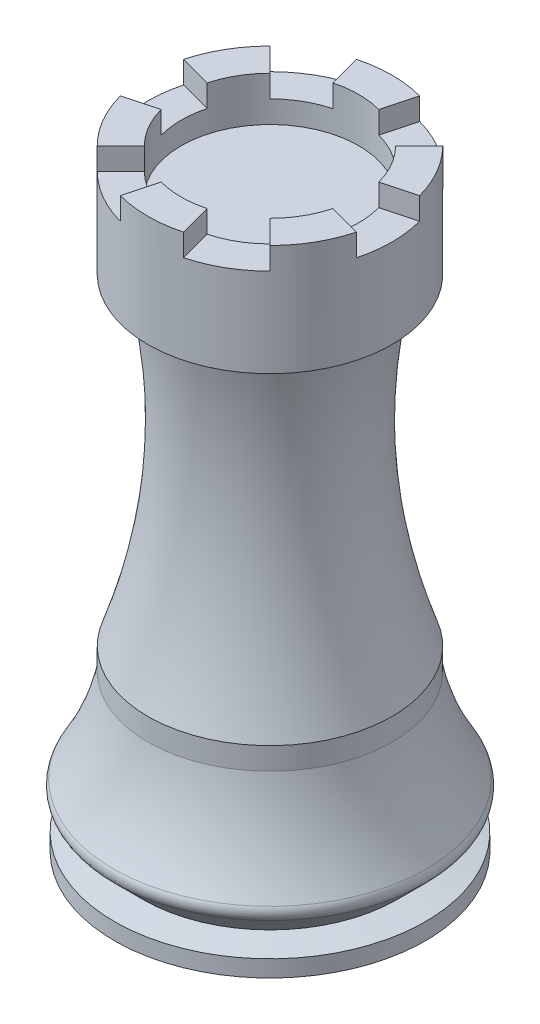
SolidWorks part; units mm, degrees
material "Maple"
ref_plane "Front Plane" through (0, 0, 0) normal (0, 0, 1) x (1, 0, 0)
ref_plane "Top Plane" through (0, 0, 0) normal (0, 1, 0) x (1, 0, 0)
ref_plane "Right Plane" through (0, 0, 0) normal (1, 0, 0) x (0, 0, -1)
sketch "bottom design" plane through (0, 0, 0) normal (0, 0, 1) x (1, 0, 0)
  line L0 (0, 0) -> (0, 50)
  line L1 (0, 0) -> (12, 0)
  line L2 (12, 0) -> (12, 3.0957) construction
  line L3 (0, 36) -> (9, 36) construction
  line L4 (9, 36) -> (9, 32.5) construction
  line L5 (9, 32.5) -> (0, 32.5) construction
  line L6 (12, 0) -> (12, 1.5)
  line L7 (12, 1.5) -> (9.8747, 1.8747)
  line L9 (0, 43) -> (3.5, 36.9378) construction
  line L11 (11, 33.5) -> (5, 32.5)
  line L13 (7, 14) -> (7, 16)
  line L14 (9.8747, 1.8747) -> (13, 5)
  line L16 (12, 3.0957) -> (12, 0) construction
  line L18 (3.5, 36.9378) -> (4.6918, 35.9378)
  line L19 (4.6918, 35.9378) -> (11, 33.5)
  arc A0 (0, 50) -> (0, 36) centre (0, 43) cw construction
  arc A1 (0, 50) -> (3.5, 36.9378) centre (0, 43) cw
  spline S0 degree 2 poles (12, 3.0957) (2.5166, 14.8814) (5, 32.5) knots 0 0 0 1 1 1 construction
  spline S1 degree 2 poles (7, 14) (9.1788, 9.005) (13, 5) knots 0 0 0 1 1 1
  spline S2 degree 3 poles (5, 32.5) (4.6326, 30.3602) (4.7601, 24.4105) (5.3037, 19.8693) (7, 16) knots 0 0 0 0 0.393038 1 1 1 1
  dimension "D4" = 55
  dimension "D15" = 31.1369
  dimension "D19" = 3.0957
  dimension "D1" = 12
  dimension "D2" = 50
  dimension "D3" = 14
  dimension "D5" = 3.5
  dimension "D7" = 100
  dimension "D8" = 30
  dimension "D9" = 1.5
  dimension "D10" = 1
  dimension "D11" = 10
  dimension "D12" = 1
  dimension "D13" = 22
  dimension "D14" = 1
  dimension "D16" = 2
  dimension "D17" = 14
  dimension "D18" = 5
  dimension "D20" = 14
  dimension "D21" = 40
sketch "Sketch1" plane through (0, 0, 0) normal (0, 0, 1) x (1, 0, 0)
  line L0 (0, 0) -> (14, 0)
  line L1 (0, 0) -> (0, 55) construction
  line L2 (0, 55) -> (12, 55) construction
  line L3 (14, 0) -> (14, 1.5)
  line L4 (14, 1.5) -> (11.4497, 1.9497)
  line L5 (11.4497, 1.9497) -> (14.5, 5)
  line L6 (12, 55) -> (12, 45) construction
  line L8 (0, 55) -> (0, 0)
  line L9 (11, 16) -> (11, 14)
  line L10 (7, 14) -> (7, 16) construction
  line L11 (0, 14) -> (11, 14) construction
  line L14 (0, 45) -> (13, 45) construction
  line L15 (13, 45) -> (13, 44) construction
  line L16 (13, 44) -> (0, 44) construction
  line L21 (0, 55) -> (11, 55)
  line L22 (11, 55) -> (11, 45)
  line L23 (9, 44) -> (11, 45)
  spline S0 degree 3 poles (11, 45) (0.9738, 34.2191) (13.3479, 17.7305) (14.5, 5) knots 0 0 0 0 1 1 1 1 construction
  spline S1 degree 2 poles (11, 14) (11.8689, 9.1496) (14.5, 5) knots 0 0 0 1 1 1
  spline S3 degree 2 poles (9, 44) (6.1192, 30.1601) (11, 16) knots 0 0 0 1 1 1
  dimension "D1" = 55
  dimension "D2" = 14
  dimension "D3" = 12
  dimension "D4" = 55
  dimension "D5" = 1.5
  dimension "D6" = 0.5
  dimension "D7" = 55
  dimension "D8" = 5
  dimension "D9" = 100
  dimension "D10" = 10
  dimension "D12" = 11
  dimension "D11" = 1
  dimension "D15" = 13
  dimension "D14" = 9
  dimension "D16" = 1
  dimension "D13" = 11
revolve "Revolve1" add sketch "Sketch1" angle 360 about L8
fillet "Fillet1" radius 1 1 edges at (-14.5, 5, 0)
sketch "Sketch2" plane through (0, 55, 0) normal (0, 1, 0) x (1, 0, 0)
  circle A0 centre (0, 0) radius 8
  circle A1 centre (0, 0) radius 11 construction
  dimension "D1" = 3
extrude "Cut-Extrude1" cut sketch "Sketch2" against normal blind 4
sketch "Sketch3" plane through (0, 0, 0) normal (0, 0, 1) x (1, 0, 0)
  line L0 (0, 0) -> (0, 56.7457) construction
  line L1 (11, 55) -> (8, 55)
  line L2 (11, 55) -> (11, 53)
  line L3 (11, 53) -> (8, 53)
  line L4 (8, 55) -> (8, 53)
  dimension "D1" = 2
  dimension "D2" = 3
revolve "Cut-Revolve1" cut sketch "Sketch3" angle 30 mid plane about L0
pattern_circular "CirPattern1" count 6 over 360 about axis through (0, 0, 0) along (0, 1, 0) of "Cut-Revolve1"
equation "\"height\" = 55mm"
equation "\"baseRadius\"= 14mm"
equation "\"upperRadius\"= 12mm"
equation "\"D1@Sketch1\"=\"height\""
equation "\"D2@Sketch1\"=\"baseRadius\""
equation "\"D3@Sketch1\"=\"upperRadius\""
equation "\"D4@Sketch1\"=\"height\""
equation "\"D12@Sketch1\"=(\"baseRadius\"/2)+4"
equation "\"D15@Sketch1\"=\"upperRadius\"+1"
equation "\"castleHeight\"= 2mm"
equation "\"D10@Sketch1\"= 8 + \"castleHeight\""
equation "\"D1@Sketch3\"=\"castleHeight\""
equation "\"D1@Cut-Extrude1\"=\"castleHeight\"*2"
